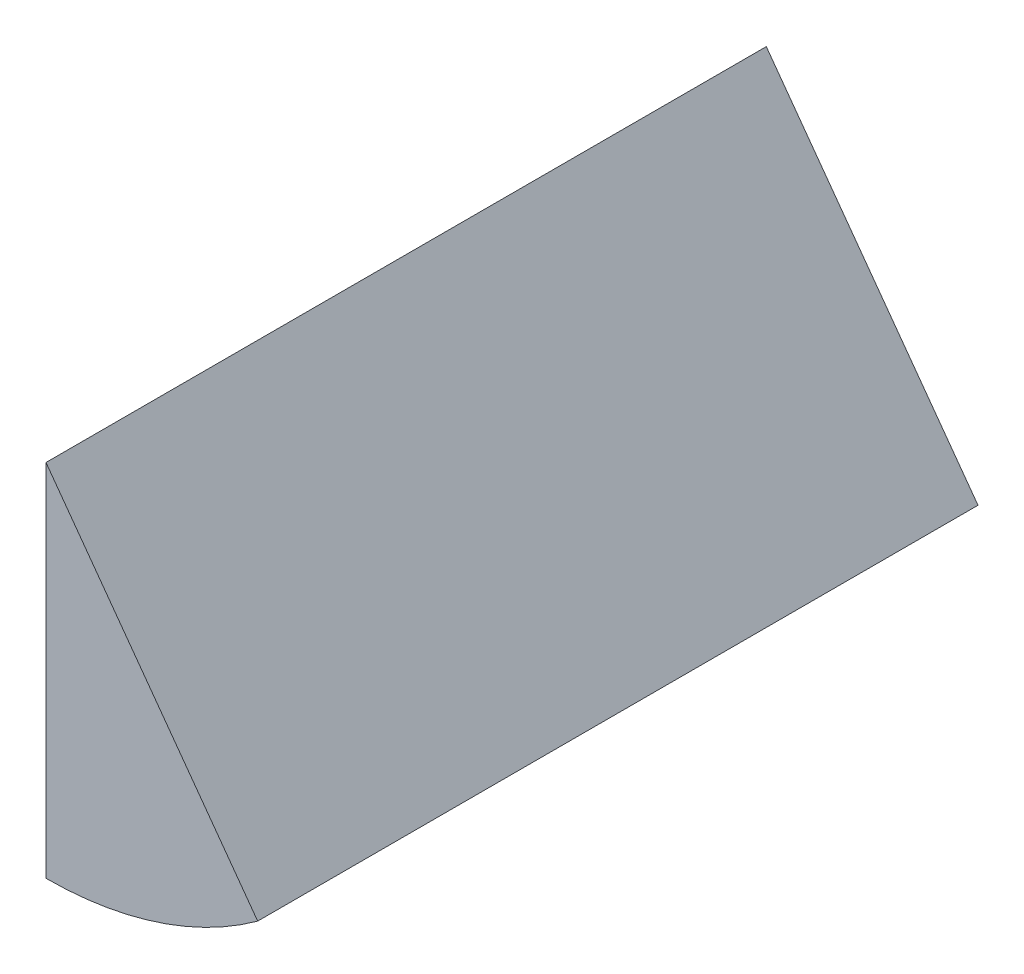
SolidWorks part; units mm, degrees
ref_plane "Alzado" through (0, 0, 0) normal (0, 0, 1) x (1, 0, 0)
ref_plane "Planta" through (0, 0, 0) normal (0, 1, 0) x (1, 0, 0)
ref_plane "Vista lateral" through (0, 0, 0) normal (1, 0, 0) x (0, 0, -1)
sketch "Croquis1" plane through (0, 0, 0) normal (0, 0, 1) x (1, 0, 0)
  line L0 (0, 0) -> (0, -25)
  line L1 (0, 0) -> (14.6946, -20.2254)
  arc A0 (0, -25) -> (14.6946, -20.2254) centre (0, 0) ccw
  dimension "D1" = 50
  dimension "D2" = 36
extrude "Saliente-Extruir1" add sketch "Croquis1" along normal blind 50
sketch "Croquis2" plane through (0, 0, 0) normal (0, 0, -1) x (-1, 0, 0)
  circle A0 centre (-5.9398, -18.149) radius 5.032
extrude "Cortar-Extruir1" cut sketch "Croquis2" against normal blind 10 contours A0
